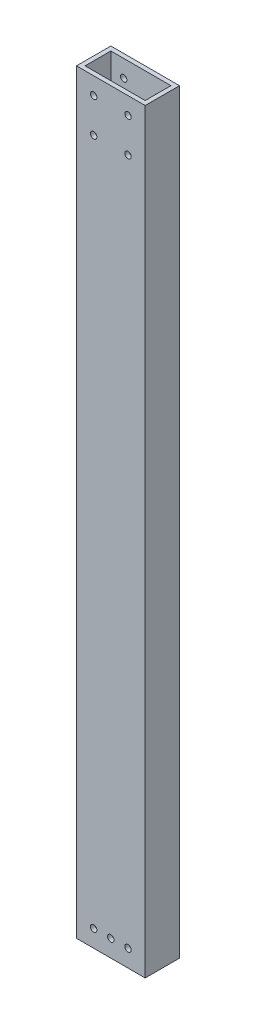
SolidWorks part; units mm, degrees
ref_plane "Front Plane" through (0, 0, 0) normal (0, 0, 1) x (1, 0, 0)
ref_plane "Top Plane" through (0, 0, 0) normal (0, 1, 0) x (1, 0, 0)
ref_plane "Right Plane" through (0, 0, 0) normal (1, 0, 0) x (0, 0, -1)
sketch "Sketch1" plane through (0, 0, 0) normal (0, 1, 0) x (1, 0, 0)
  line L1 (25.4, 12.7) -> (-25.4, 12.7)
  line L2 (25.4, 12.7) -> (25.4, -12.7)
  line L3 (25.4, -12.7) -> (-25.4, -12.7)
  line L4 (-25.4, 12.7) -> (-25.4, -12.7)
  line L5 (0, -12.7) -> (0, 12.7) construction
  line L6 (25.4, 0) -> (-25.4, 0) construction
  point P0 (0, 0)
  dimension "D1" = 50.8
  dimension "D2" = 25.4
extrude "Boss-Extrude1" add sketch "Sketch1" along normal mid plane 558.8
shell "Shell1" thickness 3.175
sketch "Sketch2" plane through (0, 0, -12.7) normal (0, 0, -1) x (-1, 0, 0)
  line L0 (-12.7, -266.7) -> (12.7, -266.7) construction
  line L1 (-25.4, -279.4) -> (25.4, -279.4) construction
  line L2 (0, 0) -> (50000, 0) construction
  line L3 (12.7, 266.7) -> (-12.7, 241.3) construction
  line L4 (-25.4, 279.4) -> (25.4, 279.4) construction
  circle A0 centre (-12.7, -266.7) radius 2.3813
  circle A1 centre (0, -266.7) radius 2.3813
  circle A2 centre (12.7, -266.7) radius 2.3813
  circle A3 centre (-12.7, 266.7) radius 2.3813
  circle A4 centre (-12.7, 241.3) radius 2.3812
  circle A5 centre (12.7, 241.3) radius 2.3812
  circle A6 centre (12.7, 266.7) radius 2.3813
  point P9 (0, -266.7)
  point P22 (0, 0)
  point P23 (0, 0)
  point P25 (0, 254)
  point P26 (30.4135, 241.6089)
  point P27 (0, 0)
  point P28 (12.7, 237.0505)
  point P29 (0, 0)
  point P30 (-12.8914, 237.8399)
  point P31 (0, 0)
  point P32 (-12.7, 266.3786)
  dimension "D2" = 4.7625
  dimension "D1" = 25.4
  dimension "D3" = 12.7
  dimension "D4" = 25.4
  dimension "D5" = 25.4
  dimension "D6" = 12.7
extrude "Cut-Extrude1" cut sketch "Sketch2" against normal through all
